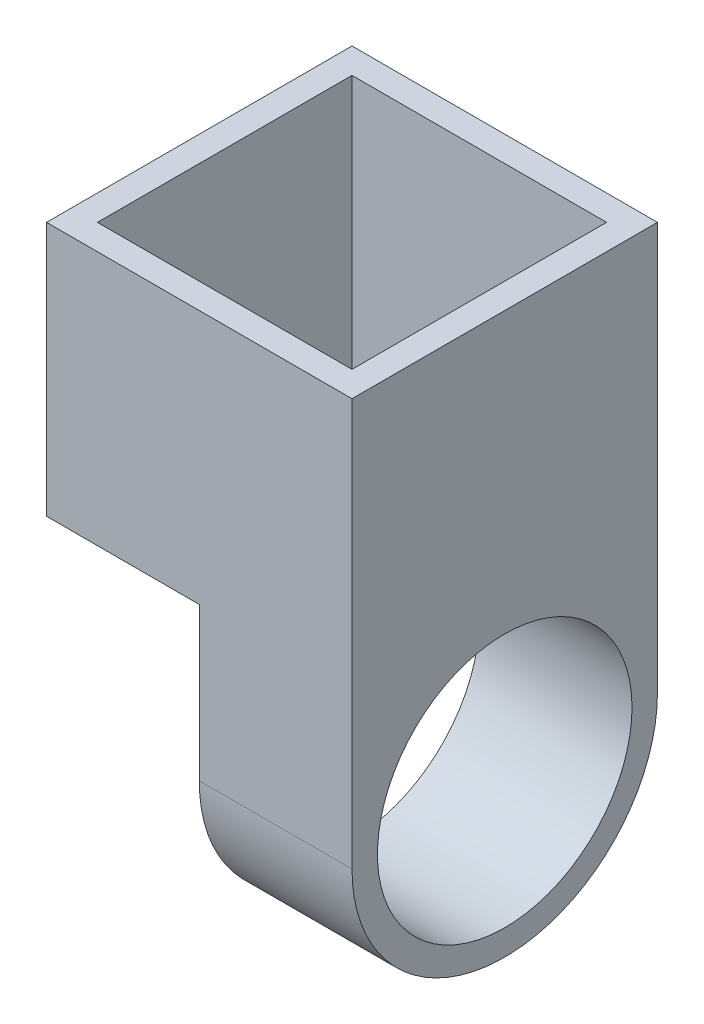
SolidWorks part; units mm, degrees
material "镀铬不锈钢"
ref_plane "前视基准面" through (0, 0, 0) normal (0, 0, 1) x (1, 0, 0)
ref_plane "上视基准面" through (0, 0, 0) normal (0, 1, 0) x (1, 0, 0)
ref_plane "右视基准面" through (0, 0, 0) normal (1, 0, 0) x (0, 0, -1)
other "Configuration Table"
sketch "草图1" plane through (0, 0, 0) normal (0, 1, 0) x (1, 0, 0)
  line L9 (-5, 5) -> (5, 5)
  line L10 (-5, 5) -> (-5, -5)
  line L11 (-5, -5) -> (5, -5)
  line L12 (5, 5) -> (5, -5)
  line L13 (-5, 5) -> (5, -5) construction
  line L14 (-5, -5) -> (5, 5) construction
  line L15 (-6, 6) -> (6, 6)
  line L16 (-6, 6) -> (-6, -6)
  line L17 (-6, -6) -> (6, -6)
  line L18 (6, 6) -> (6, -6)
  line L19 (-6, 6) -> (6, -6) construction
  line L20 (-6, -6) -> (6, 6) construction
  point P0 (0, 0)
  point P7 (0, 0)
extrude "凸台-拉伸1" add sketch "草图1" along normal blind 10
sketch "草图3" plane through (6, 0, 0) normal (1, 0, 0) x (0, 0, -1)
  line L0 (-6, 0) -> (6, 0) construction
  line L1 (-6, 0) -> (6, 0)
  line L2 (6, 0) -> (6, -12)
  line L3 (6, -12) -> (-6, -12)
  line L4 (-6, -12) -> (-6, 0)
  line L5 (-6, 0) -> (6, -12)
  line L6 (-6, -6) -> (6, -6)
  arc A2 (-6, -6) -> (6, -6) centre (0, -6) ccw
  line M7 (-6, 0) -> (6, 0)
extrude "凸台-拉伸2" add sketch "草图3" against normal blind 6 contours L4 L6 L5 | L5 L6 L2 M7 | L6 A2 L5 | L5 A2 L6
sketch "草图4" plane through (6, 0, 0) normal (1, 0, 0) x (0, 0, -1)
  circle A1 centre (0, -6) radius 5
extrude "切除-拉伸1" cut sketch "草图4" against normal blind 6
